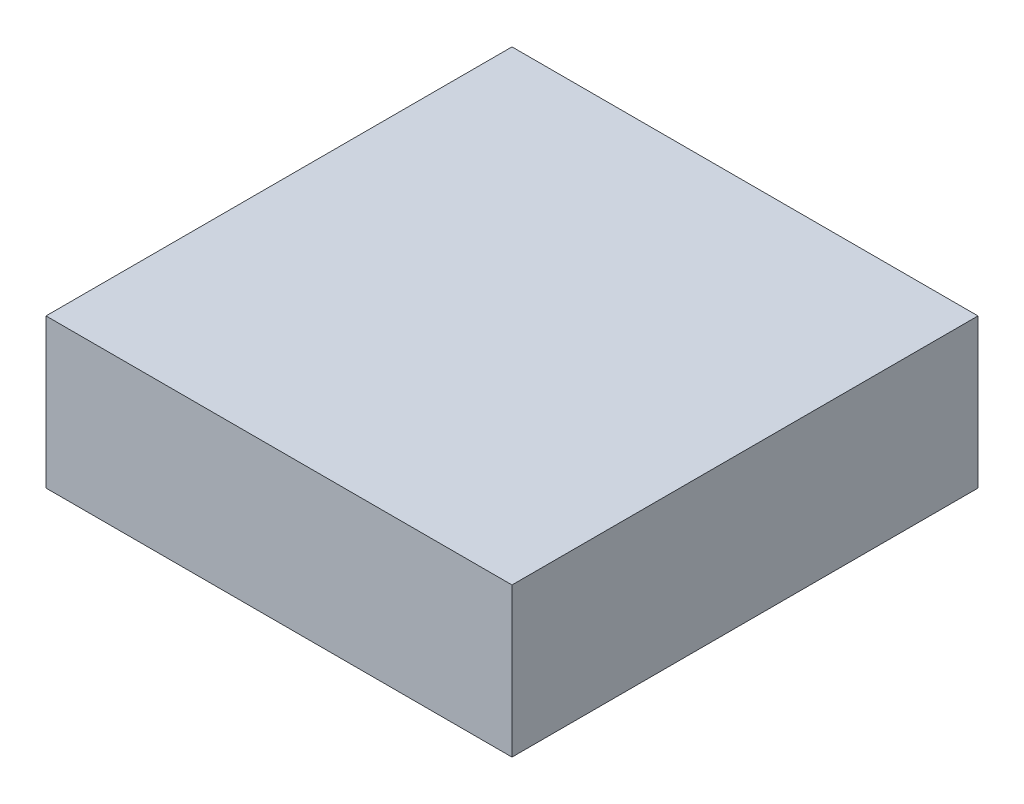
SolidWorks part; units mm, degrees
ref_plane "Front Plane" through (0, 0, 0) normal (0, 0, 1) x (1, 0, 0)
ref_plane "Top Plane" through (0, 0, 0) normal (0, 1, 0) x (1, 0, 0)
ref_plane "Right Plane" through (0, 0, 0) normal (1, 0, 0) x (0, 0, -1)
sketch "Sketch1" plane through (0, 0, 0) normal (0, 1, 0) x (1, 0, 0)
  line L1 (-6.35, -6.35) -> (6.35, -6.35)
  line L2 (-6.35, -6.35) -> (-6.35, 6.35)
  line L3 (-6.35, 6.35) -> (6.35, 6.35)
  line L4 (6.35, -6.35) -> (6.35, 6.35)
  line L5 (-6.35, -6.35) -> (6.35, 6.35) construction
  line L6 (-6.35, 6.35) -> (6.35, -6.35) construction
  point P0 (0, 0)
extrude "Boss-Extrude1" add sketch "Sketch1" along normal blind 4.064
